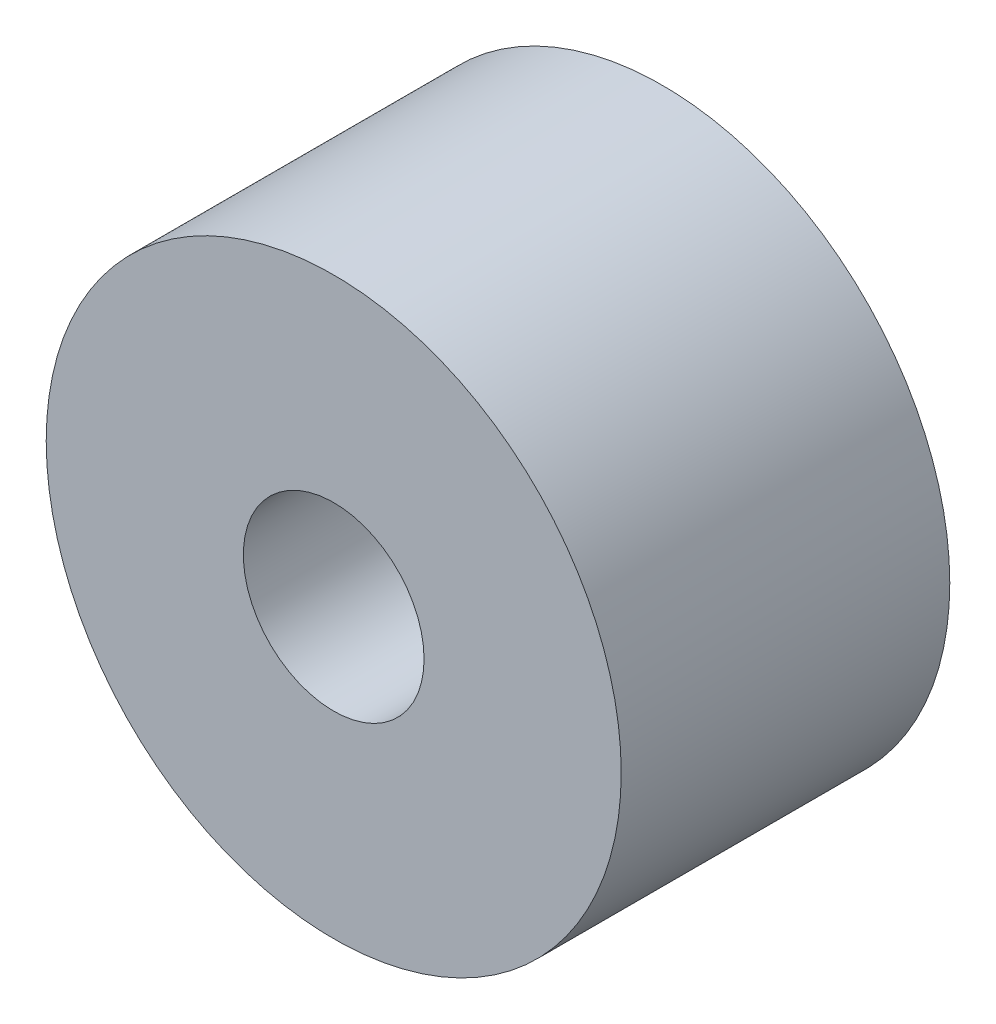
SolidWorks part; units mm, degrees
ref_plane "Front Plane" through (0, 0, 0) normal (0, 0, 1) x (1, 0, 0)
ref_plane "Top Plane" through (0, 0, 0) normal (0, 1, 0) x (1, 0, 0)
ref_plane "Right Plane" through (0, 0, 0) normal (1, 0, 0) x (0, 0, -1)
sketch "Sketch1" plane through (0, 0, 0) normal (0, 0, 1) x (1, 0, 0)
  circle A0 centre (0, 0) radius 1.375
  circle A1 centre (0, 0) radius 4.375
  dimension "D1" = 2.75
  dimension "D2" = 3
extrude "Boss-Extrude1" add sketch "Sketch1" along normal blind 5
